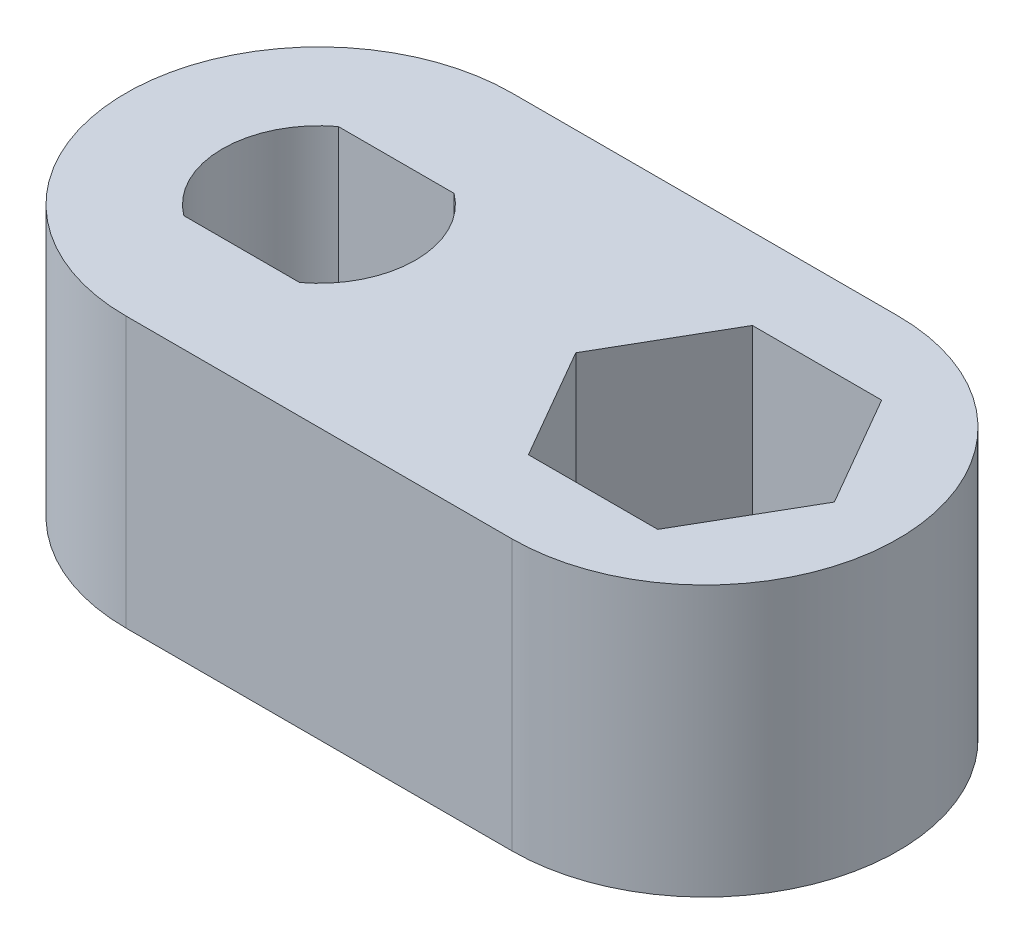
SolidWorks part; units mm, degrees
ref_plane "前视基准面" through (0, 0, 0) normal (0, 0, 1) x (1, 0, 0)
ref_plane "上视基准面" through (0, 0, 0) normal (0, 1, 0) x (1, 0, 0)
ref_plane "右视基准面" through (0, 0, 0) normal (1, 0, 0) x (0, 0, -1)
other "Configuration Table"
sketch "草图1" plane through (0, 0, 0) normal (0, 1, 0) x (1, 0, 0)
  line L0 (0, 0) -> (10, 0) construction
  line L1 (0, 5) -> (10, 5)
  line L2 (0, -5) -> (10, -5)
  line L3 (0.4876, 0.9628) -> (-0.4876, 0.9628)
  line L4 (0.4876, -0.9628) -> (-0.4876, -0.9628)
  arc A0 (0, 5) -> (0, -5) centre (0, 0) ccw
  arc A1 (10, -5) -> (10, 5) centre (10, 0) ccw
  circle A2 centre (0, 0) radius 1.0792
  point P3 (5, 0)
  dimension "D1" = 10
  dimension "D2" = 10
extrude "凸台-拉伸2" add sketch "草图1" along normal blind 7
sketch "草图2" plane through (0, 7, 0) normal (0, 1, 0) x (1, 0, 0)
  line L0 (0, 0) -> (-2.1636, 0) construction
  line L1 (-1.5, 2) -> (1.5, 2)
  line L2 (-1.5, -2) -> (1.5, -2)
  circle A0 centre (0, 0) radius 2.5
  dimension "D1" = 5
  dimension "D2" = 4
extrude "切除-拉伸1" cut sketch "草图2" against normal blind 4
sketch "草图4" plane through (0, 0, 0) normal (0, -1, 0) x (-1, 0, 0)
  point P0 (0, 0)
hole_wizard "M3 六角凹锥坑螺钉的锥形沉头孔1" positions "草图4" profile "草图5" countersink size "M3" standard "ISO" end condition through all
sketch "草图5" plane through (0, 0, 0) normal (1, 0, 0) x (0, 0, -1)
  line L0 (0, 0) -> (0, 7)
  line L1 (0, 7) -> (1.7, 7)
  line L2 (1.7, 7) -> (1.7, 1.66)
  line L3 (1.7, 1.66) -> (3.36, 0)
  line L5 (3.36, 0) -> (0, 0)
  line L6 (-1.7, 1.66) -> (-3.36, 0) construction
  line L11 (0, -6.35) -> (0, 107.95) construction
  dimension "通孔孔直径" = 3.4
  dimension "通孔孔深度" = 7
  dimension "近端锥形沉头孔直径" = 6.72
  dimension "近端锥形沉头孔角度" = 90
sketch "草图6" plane through (0, 7, 0) normal (0, 1, 0) x (1, 0, 0)
  point P0 (10, 0)
hole_wizard "孔1" positions "草图6" profile "草图7" legacy
sketch "草图7" plane through (10, 7, 0) normal (1, 0, 0) x (0, 0, 1)
  line L0 (0, 0) -> (0, 10)
  line L1 (0, 10) -> (2.075, 10)
  line L2 (2.075, 10) -> (2.075, 0)
  line L3 (2.075, 0) -> (0, 0)
  line L4 (0, 110) -> (0, -10) construction
  dimension "直径" = 4.15
  dimension "深度" = 10
sketch "草图8" plane through (0, 7, 0) normal (0, 1, 0) x (1, 0, 0)
  line L0 (0, 5) -> (10, 5) construction
  line L1 (13.3486, 0) -> (11.6743, 2.9)
  line L2 (11.6743, 2.9) -> (8.3257, 2.9)
  line L3 (8.3257, 2.9) -> (6.6514, 0)
  line L4 (6.6514, 0) -> (8.3257, -2.9)
  line L5 (8.3257, -2.9) -> (11.6743, -2.9)
  line L6 (11.6743, -2.9) -> (13.3486, 0)
  circle A0 centre (10, 0) radius 2.9 construction
  dimension "D1" = 5.8
extrude "切除-拉伸2" cut sketch "草图8" against normal blind 5
